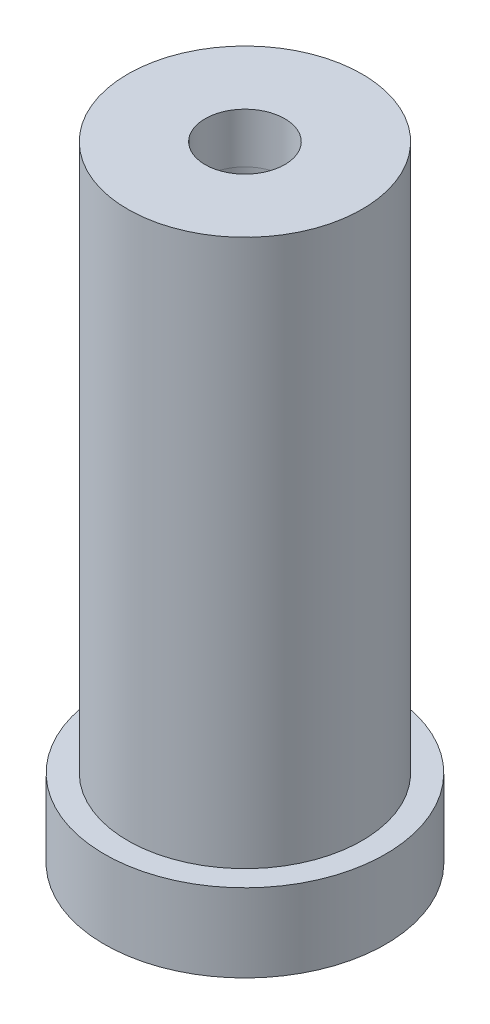
SolidWorks part; units mm, degrees
material "K110"
ref_plane "Front Plane" through (0, 0, 0) normal (0, 0, 1) x (1, 0, 0)
ref_plane "Top Plane" through (0, 0, 0) normal (0, 1, 0) x (1, 0, 0)
ref_plane "Right Plane" through (0, 0, 0) normal (1, 0, 0) x (0, 0, -1)
sketch "Sketch1" plane through (0, 0, 0) normal (0, 0, 1) x (1, 0, 0)
  line L0 (0, 0) -> (9, 0)
  line L1 (9, 0) -> (9, 5)
  line L2 (9, 5) -> (7.5, 5)
  line L3 (7.5, 5) -> (7.5, 40)
  line L4 (7.5, 40) -> (0, 40)
  line L5 (0, 40) -> (0, 0)
  line L6 (0, 45) -> (0, -5) construction
  line L7 (9.9, 0) -> (-9.9, 0) construction
  dimension "D1" = 5
  dimension "D2" = 5
  dimension "D3" = 15
  dimension "D4" = 18
  dimension "D5" = 5
  dimension "D6" = 40
revolve "Revolve1" add sketch "Sketch1" angle 360 about L6
sketch "Sketch2" plane through (0, 40, 0) normal (0, 1, 0) x (1, 0, 0)
  circle A0 centre (0, 0) radius 2.55
  dimension "D1" = 5.1
extrude "Cut-Extrude1" cut sketch "Sketch2" against normal up to next
sketch "Sketch5" plane through (0, 40, 0) normal (0, 1, 0) x (1, 0, 0)
  circle A0 centre (0, 0) radius 2.55 construction
  circle A1 centre (0, 0) radius 2.55
sketch "Sketch3" plane through (0, 0, 0) normal (0, 0, 1) x (1, 0, 0)
  line L0 (2.55, 36.8) -> (3.5136, 0)
  line L1 (2.55, 0) -> (2.55, 40) construction
  line L2 (9.9, 0) -> (-9.9, 0) construction
  line L3 (3.5136, 0) -> (2.55, 0)
  line L4 (2.55, 0) -> (2.55, 36.8)
  line L5 (7.5, 40) -> (-7.5, 40) construction
  dimension "D1" = 3.2
  dimension "D2" = 1.5
sweep "Cut-Sweep1" cut profiles "Sketch3" path "Sketch5"
